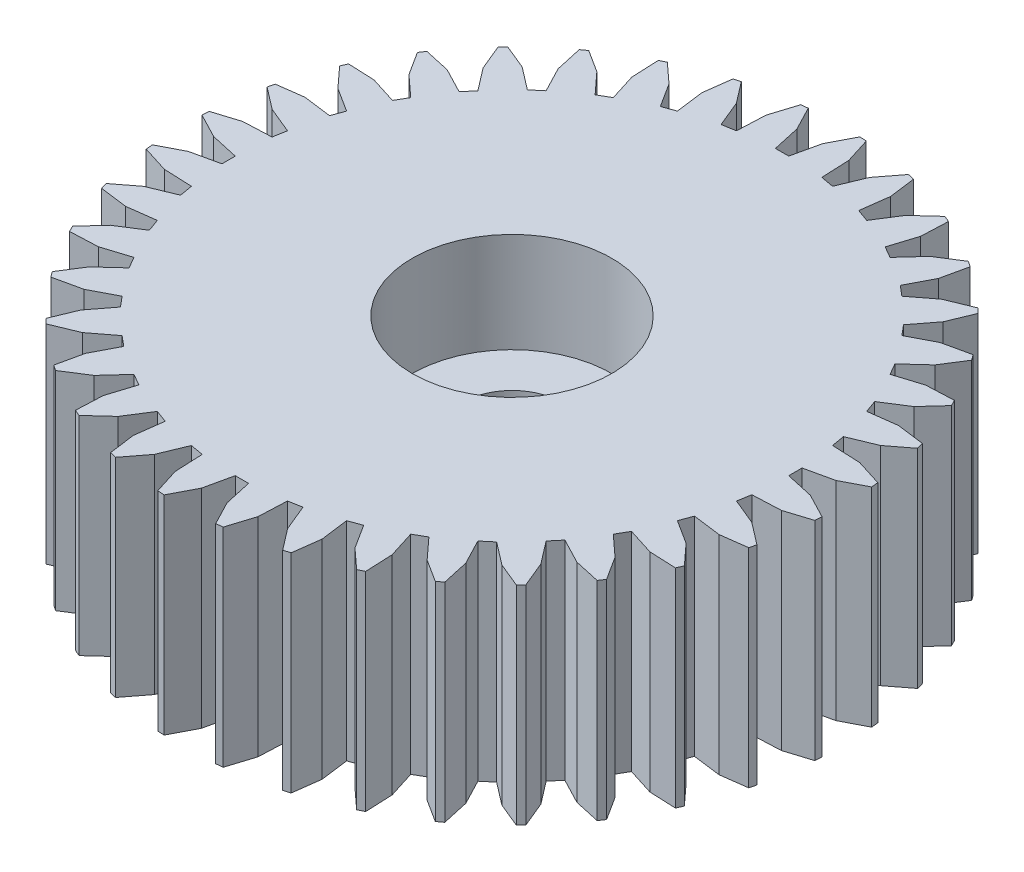
SolidWorks part; units mm, degrees
ref_plane "Front Plane" through (0, 0, 0) normal (0, 0, 1) x (1, 0, 0)
ref_plane "Top Plane" through (0, 0, 0) normal (0, 1, 0) x (1, 0, 0)
ref_plane "Right Plane" through (0, 0, 0) normal (1, 0, 0) x (0, 0, -1)
sketch "Sketch1" plane through (0, 0, 0) normal (0, 1, 0) x (1, 0, 0)
  circle A0 centre (0, 0) radius 10.0584
  dimension "D1" = 20.1168
extrude "Boss-Extrude1" add sketch "Sketch1" along normal blind 6.35
sketch "Sketch2" plane through (0, 6.35, 0) normal (0, 1, 0) x (1, 0, 0)
  circle A0 centre (0, 0) radius 1.524
  dimension "D1" = 3.048
extrude "Cut-Extrude1" cut sketch "Sketch2" against normal through all
sketch "Sketch3" plane through (0, 6.35, 0) normal (0, 1, 0) x (1, 0, 0)
  circle A0 centre (0, 0) radius 3.048
  dimension "D1" = 6.096
extrude "Cut-Extrude2" cut sketch "Sketch3" against normal blind 3.048
sketch "Sketch4" plane through (0, 0, 0) normal (0, -1, 0) x (1, 0, 0)
  line L0 (-0.9927, -10.0584) -> (-0.4064, -8.4474) construction
  line L1 (0, 0) -> (0, -10.0584) construction
  line L2 (-0.4064, -8.4474) -> (0, -8.4474)
  line L3 (0, -8.4474) -> (0.5863, -10.0584) construction
  line L4 (-0.9927, -10.0584) -> (-0.5935, -9.2915)
  line L5 (-0.5935, -9.2915) -> (-0.4064, -8.4474)
  line L6 (0, -8.4474) -> (0.1871, -9.2915)
  line L7 (0.1871, -9.2915) -> (0.5863, -10.0584)
  line L9 (0.5863, -10.0584) -> (0.9927, -10.0584) construction
  circle A0 centre (0, 0) radius 10.0584 construction
  dimension "D1" = 70
  dimension "D2" = 70
  dimension "D3" = 165
  dimension "D4" = 165
extrude "Cut-Extrude3" cut sketch "Sketch4" against normal through all flip side to cut
pattern_circular "CirPattern1" count 36 over 360 about axis through (0, 0, 0) along (0, 1, 0) of "Cut-Extrude3"
sketch "Pitch Dia" plane through (0, 0, 0) normal (0, -1, 0) x (1, 0, 0)
  circle A0 centre (0, 0) radius 9.525
  dimension "D1" = 19.05
